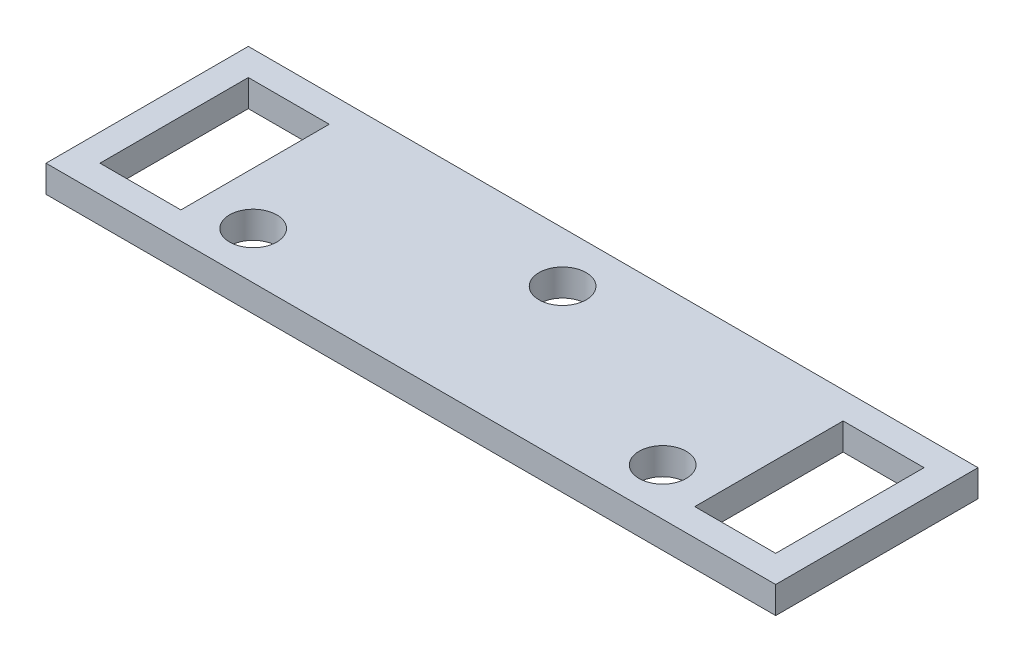
SolidWorks part; units mm, degrees
ref_plane "Front" through (0, 0, 0) normal (0, 0, 1) x (1, 0, 0)
ref_plane "Top" through (0, 0, 0) normal (0, 1, 0) x (1, 0, 0)
ref_plane "Right" through (0, 0, 0) normal (1, 0, 0) x (0, 0, -1)
sketch "Sketch1" plane through (0, 0, 0) normal (0, 1, 0) x (1, 0, 0)
  line L1 (-25.4736, 8.3194) -> (28.6264, 8.3194)
  line L2 (-25.4736, 8.3194) -> (-25.4736, -6.6806)
  line L3 (-25.4736, -6.6806) -> (28.6264, -6.6806)
  line L4 (28.6264, 8.3194) -> (28.6264, -6.6806)
  line L5 (-23.4736, 6.3194) -> (-17.4736, 6.3194)
  line L6 (-23.4736, 6.3194) -> (-23.4736, -4.6806)
  line L7 (-23.4736, -4.6806) -> (-17.4736, -4.6806)
  line L8 (-17.4736, 6.3194) -> (-17.4736, -4.6806)
  line L9 (20.6264, 6.3194) -> (26.6264, 6.3194)
  line L10 (20.6264, 6.3194) -> (20.6264, -4.6806)
  line L11 (20.6264, -4.6806) -> (26.6264, -4.6806)
  line L12 (26.6264, 6.3194) -> (26.6264, -4.6806)
  circle A0 centre (16.7564, -3.1906) radius 1.75
  circle A1 centre (-13.6036, -3.1906) radius 1.75
  circle A2 centre (1.5764, 4.5694) radius 1.75
  dimension "D1" = 3.5
  dimension "D2" = 3.5
  dimension "D4" = 3.5
  dimension "D3" = 30.36
  dimension "D5" = 15.18
  dimension "D6" = 38.1
  dimension "D7" = 2
  dimension "D8" = 6
  dimension "D9" = 11
  dimension "D10" = 6
  dimension "D11" = 11
  dimension "D12" = 2
  dimension "D13" = 2
  dimension "D14" = 2
  dimension "D15" = 27.05
  dimension "D16" = 2
  dimension "D17" = 7.76
  dimension "D18" = 3.75
extrude "Boss-Extrude1" add sketch "Sketch1" along normal blind 2
